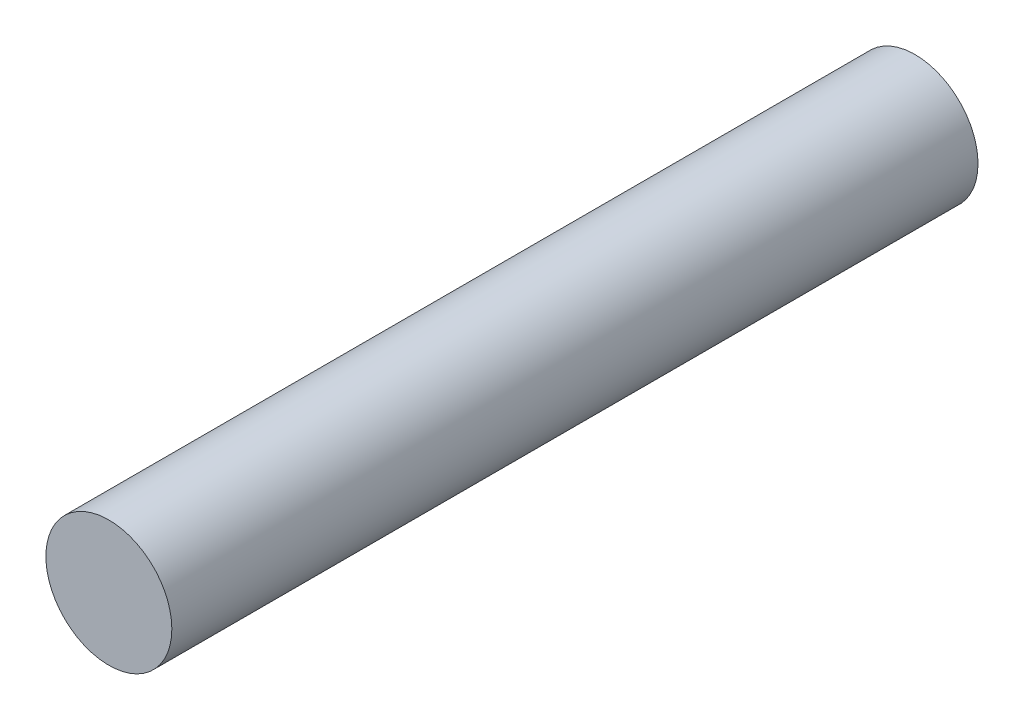
SolidWorks part; units mm, degrees
ref_plane "Front Plane" through (0, 0, 0) normal (0, 0, 1) x (1, 0, 0)
ref_plane "Top Plane" through (0, 0, 0) normal (0, 1, 0) x (1, 0, 0)
ref_plane "Right Plane" through (0, 0, 0) normal (1, 0, 0) x (0, 0, -1)
sketch "Sketch1" plane through (0, 0, 0) normal (0, 0, 1) x (1, 0, 0)
  circle A0 centre (0, 0) radius 12.5
  dimension "D1" = 25
extrude "Boss-Extrude1" add sketch "Sketch1" along normal blind 160
